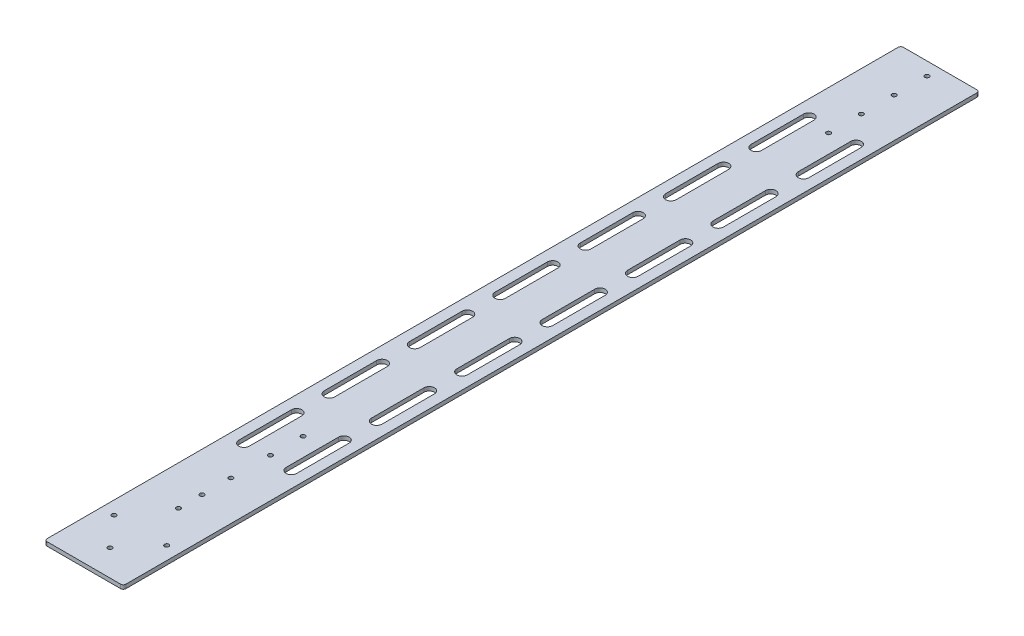
SolidWorks part; units mm, degrees
ref_plane "前视基准面" through (0, 0, 0) normal (0, 0, 1) x (1, 0, 0)
ref_plane "上视基准面" through (0, 0, 0) normal (0, 1, 0) x (1, 0, 0)
ref_plane "右视基准面" through (0, 0, 0) normal (1, 0, 0) x (0, 0, -1)
sketch "草图1" plane through (0, 0, 0) normal (0, 1, 0) x (1, 0, 0)
  line L1 (-30, -326) -> (30, -326)
  line L2 (-30, -326) -> (-30, 326)
  line L3 (-30, 326) -> (30, 326)
  line L4 (30, -326) -> (30, 326)
  line L5 (-30, -326) -> (30, 326) construction
  line L6 (-30, 326) -> (30, -326) construction
  point P0 (0, 0)
  dimension "D1" = 652
  dimension "D2" = 60
extrude "凸台-拉伸1" add sketch "草图1" along normal blind 3
sketch "草图2" plane through (0, 3, 0) normal (0, 1, 0) x (1, 0, 0)
  line L0 (0, 358.6854) -> (0, -383.7976) construction
  line L1 (-30, -326) -> (30, -326) construction
  line L2 (30, 326) -> (-30, 326) construction
  circle A0 centre (0, -306) radius 1.65
  circle A1 centre (0, -236) radius 1.65
  circle A2 centre (0, -184) radius 1.65
  circle A3 centre (0, -159) radius 1.65
  circle A4 centre (0, 316) radius 1.65
  circle A5 centre (0, 291) radius 1.65
  circle A6 centre (0, 266) radius 1.65
  circle A7 centre (0, 241) radius 1.65
  dimension "D1" = 3.3
  dimension "D2" = 3.3
  dimension "D3" = 20
  dimension "D4" = 70
  dimension "D7" = 3.3
  dimension "D8" = 3.3
  dimension "D9" = 10
  dimension "D10" = 25
  dimension "D11" = 3.3
  dimension "D12" = 3.3
  dimension "D13" = 60
  dimension "D14" = 25
  dimension "D15" = 3.3
  dimension "D16" = 3.3
  dimension "D5" = 25
  dimension "D6" = 142
extrude "切除-拉伸1" cut sketch "草图2" against normal blind 3
fillet "圆角1" radius 2 4 edges at (30, 1.5, 326) (-30, 1.5, 326) (-30, 1.5, -326) (30, 1.5, -326)
sketch "草图4" plane through (0, 3, 0) normal (0, 1, 0) x (1, 0, 0)
  line L0 (-80.8394, -283) -> (161.0929, -283) construction
  line L1 (-28, -326) -> (28, -326) construction
  line L2 (30, -324) -> (30, 324) construction
  circle A0 centre (20, -283) radius 1.65
  circle A1 centre (-20, -283) radius 1.65
  dimension "D2" = 40
  dimension "D3" = 10
  dimension "D4" = 3.3
  dimension "D5" = 3.3
  dimension "D1" = 43
extrude "切除-拉伸2" cut sketch "草图4" against normal blind 10
sketch "草图5" plane through (0, 3, 0) normal (0, 1, 0) x (1, 0, 0)
  line L0 (18, 364.9159) -> (18, -415.5283) construction
  line L1 (-18, 377.0629) -> (-18, -433.7488) construction
  line L2 (30, -324) -> (30, 324) construction
  line L3 (-30, 324) -> (-30, -324) construction
  line L4 (18, -186) -> (18, -146) construction
  line L5 (14, -186) -> (14, -146)
  line L6 (22, -186) -> (22, -146)
  line L7 (-28, -326) -> (28, -326) construction
  arc A0 (14, -186) -> (22, -186) centre (18, -186) ccw
  arc A1 (22, -146) -> (14, -146) centre (18, -146) ccw
  point P10 (18, -166)
  dimension "D1" = 12
  dimension "D2" = 12
  dimension "D3" = 8
  dimension "D4" = 40
  dimension "D5" = 140
extrude "切除-拉伸3" cut sketch "草图5" against normal blind 3
pattern_linear "阵列(线性)2" count 7 spacing 65 along (0, 0, -1) of "切除-拉伸3"
mirror "镜向1" about plane through (0, 0, 0) normal (1, 0, 0) of "阵列(线性)2", "切除-拉伸3"
sketch "草图6" plane through (0, 0, 0) normal (0, -1, 0) x (1, 0, 0)
  line L0 (-56.5193, 254) -> (65.3146, 254) construction
  line L1 (0, 340.3072) -> (0, 119.714) construction
  line L2 (-28, 326) -> (28, 326) construction
  line L3 (-56.5193, 214) -> (69.1351, 214) construction
  circle A0 centre (0, 254) radius 1.65
  circle A2 centre (0, 214) radius 1.65
  dimension "D4" = 3.3
  dimension "D9" = 3.3
  dimension "D1" = 72
  dimension "D3" = 0
  dimension "D6" = 112
  dimension "D8" = 0
extrude "切除-拉伸4" cut sketch "草图6" against normal blind 10
